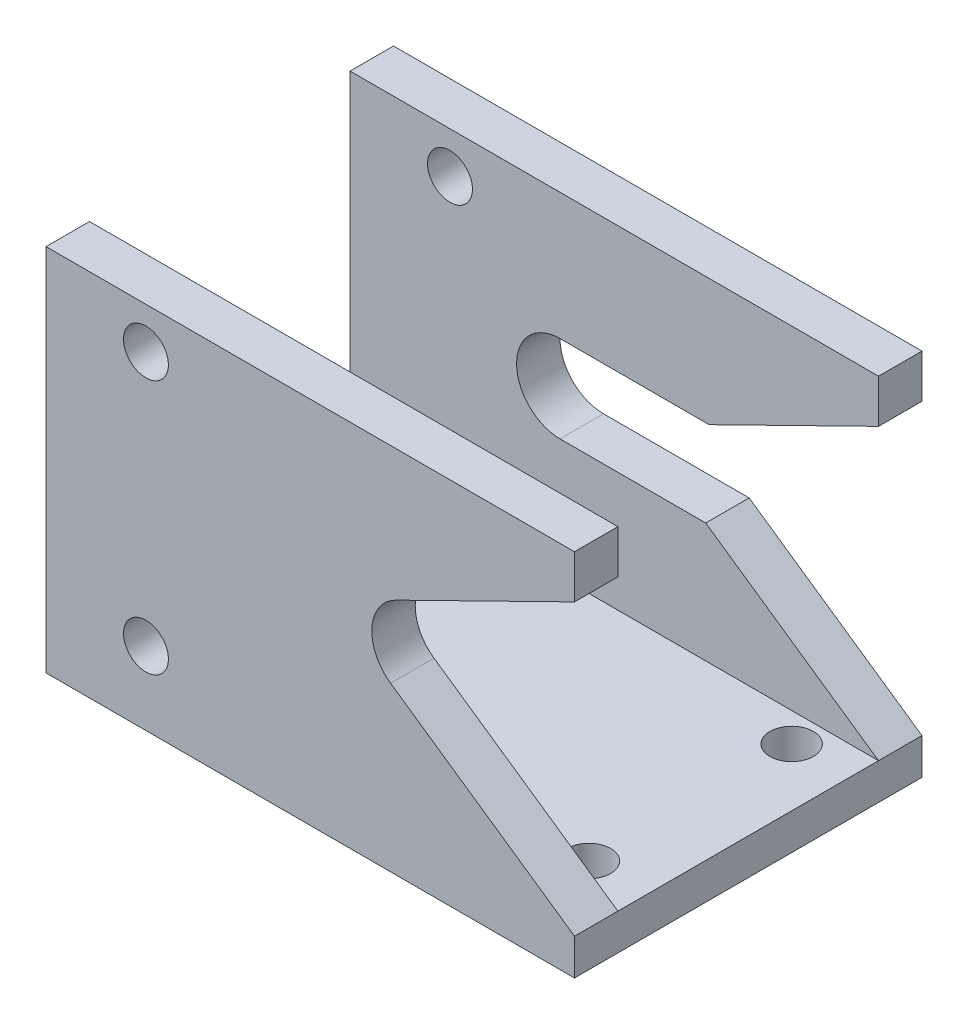
SolidWorks part; units mm, degrees
ref_plane "Front Plane" through (0, 0, 0) normal (0, 0, 1) x (1, 0, 0)
ref_plane "Top Plane" through (0, 0, 0) normal (0, 1, 0) x (1, 0, 0)
ref_plane "Right Plane" through (0, 0, 0) normal (1, 0, 0) x (0, 0, -1)
sketch "Sketch1" plane through (0, 0, 0) normal (0, 1, 0) x (1, 0, 0)
  line L1 (0, 0) -> (36.5, 0)
  line L2 (0, 0) -> (0, 24)
  line L3 (0, 24) -> (36.5, 24)
  line L4 (36.5, 0) -> (36.5, 24)
  dimension "D1" = 36.5
  dimension "D2" = 24
extrude "Boss-Extrude1" add sketch "Sketch1" along normal blind 2.5
sketch "Sketch2" plane through (0, 2.5, 0) normal (0, 1, 0) x (1, 0, 0)
  line L0 (0, 24) -> (0, 0) construction
  line L1 (0, 3) -> (36.5, 3)
  line L2 (0, 3) -> (0, 0)
  line L3 (0, 0) -> (36.5, 0)
  line L4 (36.5, 3) -> (36.5, 0)
  line L5 (36.5, 0) -> (36.5, 24) construction
  line L6 (36.5, 21) -> (0, 21)
  line L7 (36.5, 21) -> (36.5, 24)
  line L8 (36.5, 24) -> (0, 24)
  line L9 (0, 21) -> (0, 24)
  dimension "D1" = 3
  dimension "D2" = 3
extrude "Boss-Extrude2" add sketch "Sketch2" along normal blind 23
sketch "Sketch3" plane through (0, 0, 0) normal (0, 0, 1) x (1, 0, 0)
  line L0 (36.5, 25.5) -> (36.5, 0) construction
  line L1 (36.5, 25.5) -> (36.5, 0)
  line L2 (23.7942, 11.2821) -> (36.5, 2.5)
  line L3 (0, 0) -> (36.5, 0) construction
  line L4 (36.5, 22.4972) -> (24.1771, 16.4426)
  circle A0 centre (25.5, 13.75) radius 3
  circle A1 centre (6.9, 5.05) radius 1.55
  circle A2 centre (6.9, 22.65) radius 1.55
  dimension "D1" = 6
  dimension "D2" = 11
  dimension "D3" = 13.75
  dimension "D4" = 2.5
  dimension "D7" = 3.1
  dimension "D8" = 5.05
  dimension "D9" = 17.6
  dimension "D10" = 29.6
  dimension "D11" = 29.6
  dimension "D12" = 3.1
  dimension "D5" = 15.4455
  dimension "D6" = 13.73
extrude "Cut-Extrude2" cut sketch "Sketch3" against normal through all contours A0 | A0 L2 L1 L4 | A2 | A1
sketch "Sketch6" plane through (0, 2.5, 0) normal (0, 1, 0) x (1, 0, 0)
  line L0 (18.25, 24) -> (18.25, 0) construction
  line L1 (36.5, 24) -> (0, 24) construction
  line L2 (0, 0) -> (36.5, 0) construction
  line L3 (0, 12) -> (36.5, 12) construction
  line L4 (0, 21) -> (0, 3) construction
  line L5 (36.5, 3) -> (36.5, 21) construction
  circle A0 centre (4, 19) radius 1.5
  circle A1 centre (32.5, 19) radius 1.5
  circle A2 centre (32.5, 5) radius 1.5
  circle A3 centre (4, 5) radius 1.5
  dimension "D1" = 3
  dimension "D2" = 4
  dimension "D3" = 5
extrude "Cut-Extrude4" cut sketch "Sketch6" against normal through all
sketch "Sketch8" plane through (0, 0, -24) normal (0, 0, -1) x (-1, 0, 0)
  line L0 (-36.5, 25.5) -> (-36.5, 22.4972) construction
  line L2 (-36.5, 0) -> (0, 0) construction
  line L3 (-14.5, 16.75) -> (-24.8028, 16.75)
  line L4 (-36.5, 22.4972) -> (-24.1771, 16.4426) construction
  line L5 (-14.5, 10.75) -> (-24.5641, 10.75)
  line L6 (-23.7942, 11.2821) -> (-36.5, 2.5) construction
  circle A0 centre (-14.5, 13.75) radius 3
  point P14 (-14.5, 10.585)
  point P15 (0, 0)
  line M4 (-36.5, 22.4972) -> (-24.1771, 16.4426)
  arc M5 (-24.1771, 16.4426) -> (-23.7942, 11.2821) centre (-25.5, 13.75) cw
  line M6 (-23.7942, 11.2821) -> (-36.5, 2.5)
  line M8 (-36.5, 0) -> (0, 0)
  dimension "D1" = 6
  dimension "D2" = 22
  dimension "D3" = 13.75
extrude "Cut-Extrude5" cut sketch "Sketch8" against normal up to next contours A0 L3 L5 M4 M5 M6 | A0 M8
